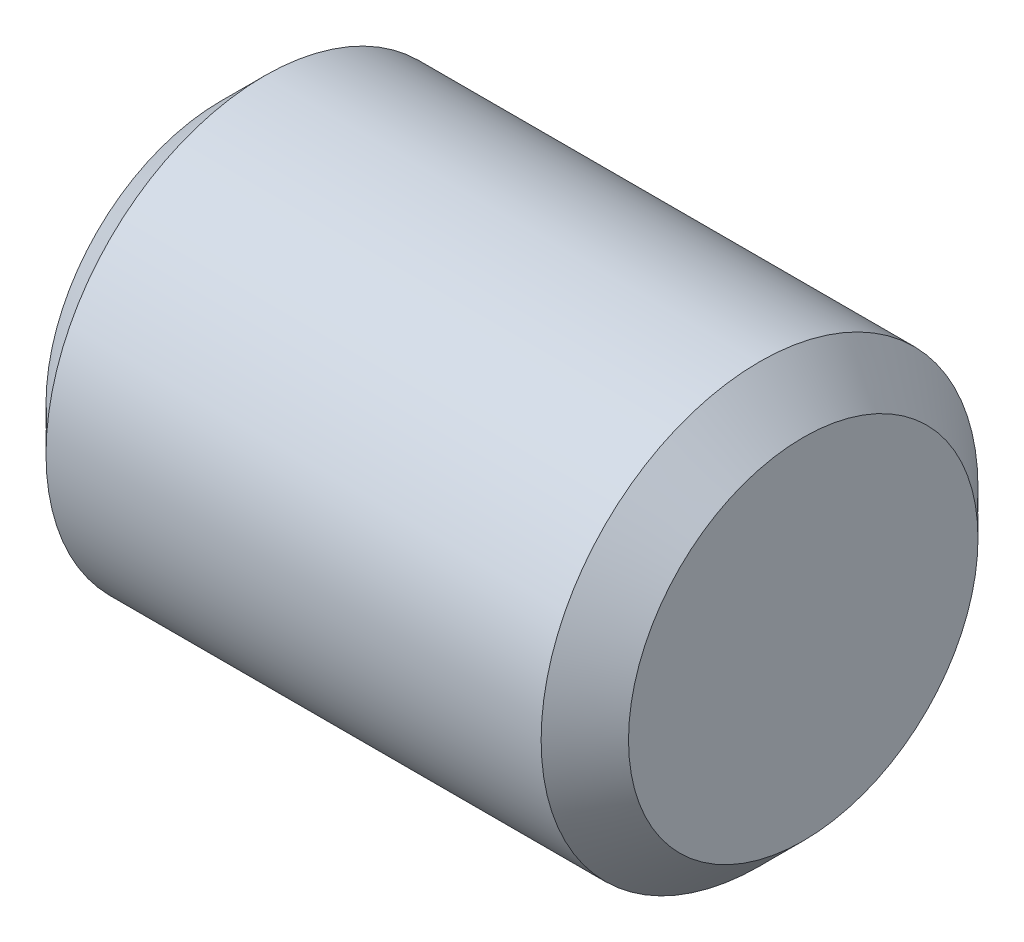
SolidWorks part; units mm, degrees
ref_plane "Front" through (0, 0, 0) normal (0, 0, 1) x (1, 0, 0)
ref_plane "Top" through (0, 0, 0) normal (0, 1, 0) x (1, 0, 0)
ref_plane "Right" through (0, 0, 0) normal (1, 0, 0) x (0, 0, -1)
sketch "Sketch1" plane through (0, 0, 0) normal (0, 0, 1) x (1, 0, 0)
  line L0 (-3.175, 0) -> (3.175, 0) construction
  line L1 (3.175, 2.3813) -> (3.175, -2.3813) construction
  line L2 (-3.175, 2.3813) -> (-3.175, -2.3813) construction
  dimension "Length" = 6.35
  dimension "Diameter" = 4.7625
sketch "Sketch2" plane through (0, 0, 0) normal (1, 0, 0) x (0, 0, -1)
  circle A0 centre (0, 0) radius 2.3813
extrude "Extrude1" add sketch "Sketch2" against normal up to vertex (3.175 mm away) and the other way up to vertex (3.175 mm away) up to point (-3.175, 2.3813, 0) other way up to point (3.175, 2.3813, 0)
chamfer "Chamfer1" distance 0.4763 angle 45 2 edges at (3.175, 0, -2.3813) (-3.175, 0, -2.3813)
equation "\"D1@Chamfer1\" = \"Diameter@Sketch1\"*.1"
